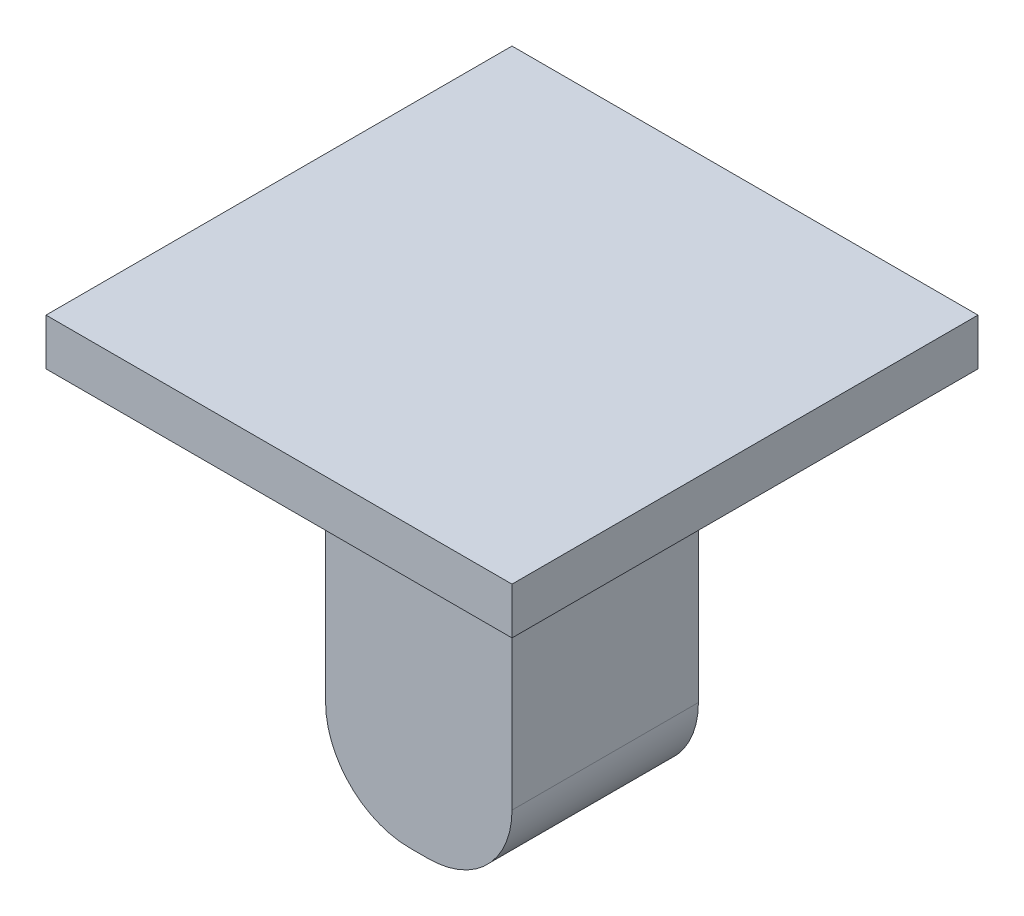
SolidWorks part; units mm, degrees
ref_plane "Plano frontal" through (0, 0, 0) normal (0, 0, 1) x (1, 0, 0)
ref_plane "Plano superior" through (0, 0, 0) normal (0, 1, 0) x (1, 0, 0)
ref_plane "Plano direito" through (0, 0, 0) normal (1, 0, 0) x (0, 0, -1)
sketch "Esboço1" plane through (0, 0, 0) normal (0, 0, 1) x (1, 0, 0)
  line L1 (9, 0) -> (11, 0)
  line L2 (0, 9) -> (0, 40)
  line L3 (0, 40) -> (20, 40)
  line L4 (20, 9) -> (20, 40)
  arc A0 (11, 0) -> (20, 9) centre (11, 9) ccw
  arc A1 (9, 0) -> (0, 9) centre (9, 9) cw
  point P9 (0, 0)
  dimension "D3" = 9
  dimension "D1" = 40
  dimension "D2" = 20
extrude "Ressalto-extrusão1" add sketch "Esboço1" along normal blind 20
sketch "Esboço2" plane through (0, 40, 0) normal (0, 1, 0) x (1, 0, 0)
  line L0 (-15, -35) -> (35, -35)
  line L5 (35, -35) -> (35, 15)
  line L6 (-15, 15) -> (35, 15)
  line L7 (-15, -35) -> (-15, 15)
extrude "Ressalto-extrusão2" add sketch "Esboço2" along normal blind 5
